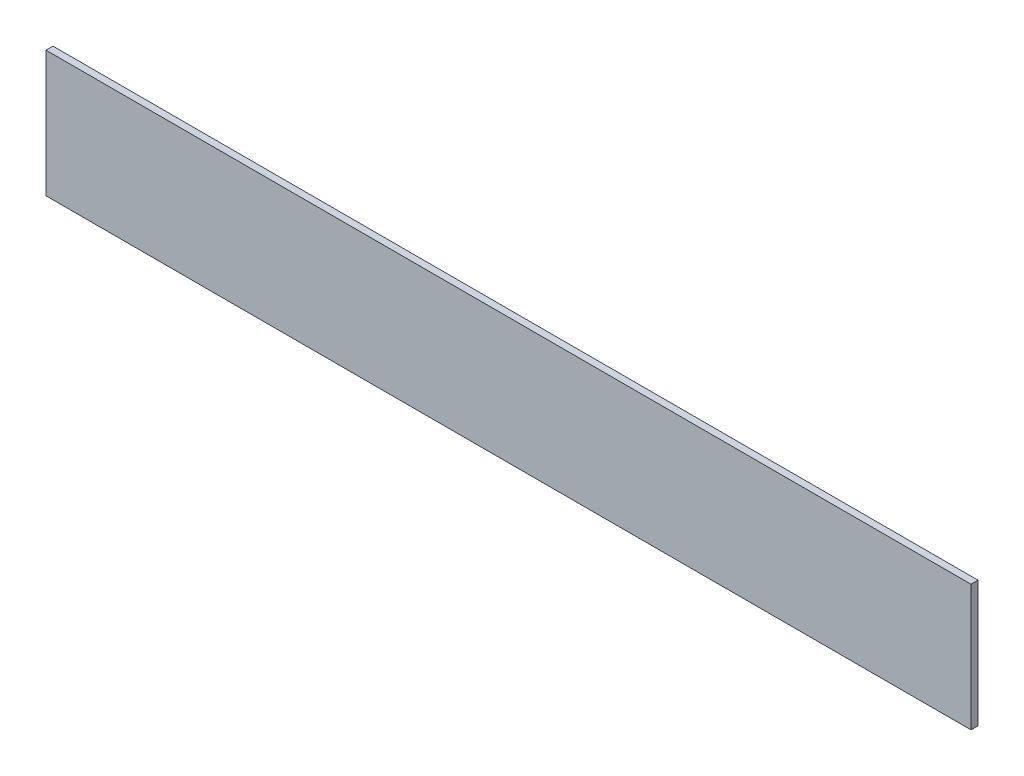
SolidWorks part; units mm, degrees
ref_plane "Front Plane" through (0, 0, 0) normal (0, 0, 1) x (1, 0, 0)
ref_plane "Top Plane" through (0, 0, 0) normal (0, 1, 0) x (1, 0, 0)
ref_plane "Right Plane" through (0, 0, 0) normal (1, 0, 0) x (0, 0, -1)
other "Configuration Table"
sketch "Sketch1" plane through (0, 0, 0) normal (0, 0, 1) x (1, 0, 0)
  line L1 (185, 552) -> (515, 552)
  line L2 (185, 552) -> (185, 597)
  line L3 (185, 597) -> (515, 597)
  line L4 (515, 552) -> (515, 597)
extrude "PACK_kalip_duvari_arka_1" add sketch "Sketch1" against normal blind 2.5 from offset 562.5 separate body
